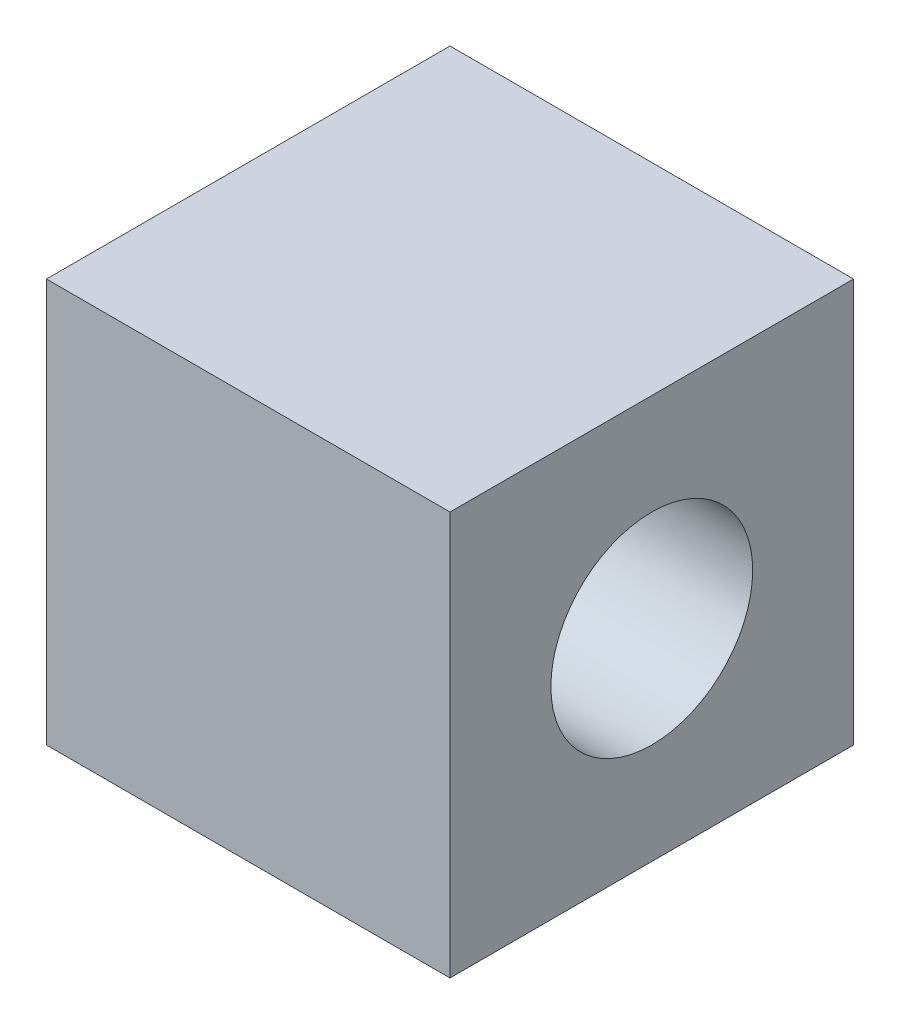
SolidWorks part; units mm, degrees
ref_plane "Front Plane" through (0, 0, 0) normal (0, 0, 1) x (1, 0, 0)
ref_plane "Top Plane" through (0, 0, 0) normal (0, 1, 0) x (1, 0, 0)
ref_plane "Right Plane" through (0, 0, 0) normal (1, 0, 0) x (0, 0, -1)
sketch "Sketch1" plane through (0, 0, 0) normal (0, 0, 1) x (1, 0, 0)
  line L1 (-25.4, -25.4) -> (25.4, -25.4)
  line L2 (-25.4, -25.4) -> (-25.4, 25.4)
  line L3 (-25.4, 25.4) -> (25.4, 25.4)
  line L4 (25.4, -25.4) -> (25.4, 25.4)
  line L5 (-25.4, -25.4) -> (25.4, 25.4) construction
  line L6 (-25.4, 25.4) -> (25.4, -25.4) construction
  point P0 (0, 0)
  dimension "D1" = 50.8
  dimension "D2" = 50.8
extrude "Boss-Extrude1" add sketch "Sketch1" along normal blind 50.8
sketch "Sketch2" plane through (25.4, 0, 0) normal (1, 0, 0) x (0, 0, -1)
  line L0 (-50.8, 0) -> (0, 0) construction
  line L1 (-50.8, -25.4) -> (-50.8, 25.4) construction
  line L2 (0, -25.4) -> (0, 25.4) construction
  circle A0 centre (-25.4, 0) radius 12.7
  dimension "D1" = 25.4
extrude "Cut-Extrude1" cut sketch "Sketch2" against normal blind 50.8
